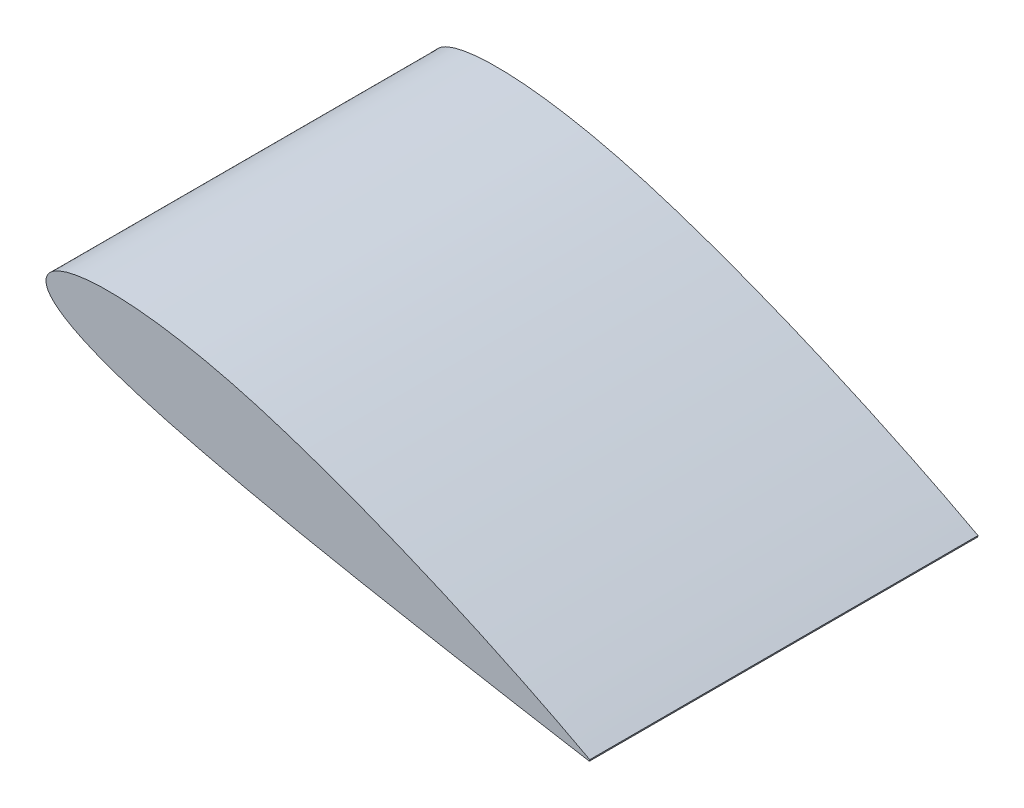
SolidWorks part; units mm, degrees
ref_plane "Płaszczyzna przednia"
ref_plane "Płaszczyzna górna" through (0, 0, 0) normal (0, 1, 0) x (1, 0, 0)
ref_plane "Płaszczyzna prawa" through (0, 0, 0) normal (1, 0, 0) x (0, 0, -1)
curve "Krzywa1"
  spline degree 3 poles (1, 0.0015, 0) (0.9991, 0.0017, 0) (0.9956, 0.0025, 0) (0.9875, 0.0044, 0) (0.9742, 0.0074, 0) (0.9556, 0.0115, 0) (0.9322, 0.0166, 0) (0.904, 0.0224, 0) (0.8713, 0.0289, 0) (0.8346, 0.0358, 0) (0.7942, 0.043, 0) (0.7505, 0.0503, 0) (0.7041, 0.0574, 0) (0.6553, 0.0643, 0) (0.6048, 0.0707, 0) (0.5531, 0.0765, 0) (0.5007, 0.0814, 0) (0.4483, 0.0853, 0) (0.3962, 0.0881, 0) (0.3451, 0.0894, 0) (0.2956, 0.089, 0) (0.2483, 0.0868, 0) (0.2039, 0.083, 0) (0.1628, 0.0776, 0) (0.1256, 0.0708, 0) (0.0927, 0.0627, 0) (0.0643, 0.0537, 0) (0.0409, 0.0439, 0) (0.0225, 0.0337, 0) (0.0093, 0.0231, 0) (0.0011, 0.0119, 0) (-0.001, -0.0001, 0) (0.0034, -0.0114, 0) (0.0135, -0.0208, 0) (0.0284, -0.0287, 0) (0.0479, -0.0355, 0) (0.0722, -0.0411, 0) (0.1009, -0.0456, 0) (0.1337, -0.0489, 0) (0.1703, -0.0511, 0) (0.2104, -0.0521, 0) (0.2535, -0.0522, 0) (0.2992, -0.0514, 0) (0.347, -0.0499, 0) (0.3967, -0.0479, 0) (0.4476, -0.0455, 0) (0.4993, -0.0424, 0) (0.5511, -0.0389, 0) (0.6024, -0.0352, 0) (0.6526, -0.0314, 0) (0.7012, -0.0275, 0) (0.7477, -0.0237, 0) (0.7915, -0.0201, 0) (0.8321, -0.0166, 0) (0.8691, -0.0134, 0) (0.9021, -0.0105, 0) (0.9307, -0.0079, 0) (0.9546, -0.0057, 0) (0.9734, -0.004, 0) (0.9871, -0.0027, 0) (0.9953, -0.0019, 0) (0.999, -0.0016, 0) (1, -0.0015, 0) knots 0 0 0 0 0.001308 0.005358 0.012063 0.021337 0.033087 0.047171 0.063441 0.081714 0.101785 0.123442 0.146433 0.170517 0.195424 0.220875 0.246594 0.272302 0.297725 0.322799 0.347029 0.370162 0.391954 0.412188 0.43067 0.447231 0.461732 0.474085 0.484276 0.492392 0.498749 0.5041 0.509453 0.51579 0.523838 0.533885 0.546005 0.560171 0.576284 0.594211 0.613803 0.634869 0.65721 0.680611 0.704835 0.729853 0.755197 0.780583 0.805729 0.830359 0.854204 0.877002 0.898494 0.918443 0.936623 0.952826 0.966868 0.978592 0.987852 0.994547 0.998596 1 1 1 1
sketch "Szkic1" plane through (0, 0, 0) normal (0, 0, 1) x (1, 0, 0)
  line L0 (699.9029, -187.9268) -> (699.3515, -189.9846)
  line L1 (16.3522, 61.0271) -> (716.3522, -126.5373) construction
  line L2 (16.3522, 61.0271) -> (-10.1518, -37.8869) construction
  line L3 (-10.1518, -37.8869) -> (689.8482, -225.4513) construction
  line L4 (716.3522, -126.5373) -> (689.8482, -225.4513) construction
  line L5 (500.002, 0) -> (0, 0) construction
  line L6 (0, 0) -> (-68.0941, 0) construction
  spline S1 degree 3 poles (699.9029, -187.9268) (699.3338, -187.6158) (697.0031, -186.3423) (691.7065, -183.5667) (682.9295, -178.9272) (670.7346, -172.5873) (655.2545, -164.638) (628.5192, -151.1881) (588.2383, -131.6047) (532.7177, -105.9919) (480.9854, -83.605) (436.2712, -65.3508) (401.1493, -51.6181) (365.4184, -38.3681) (329.4605, -25.7883) (293.553, -14.0525) (258.0259, -3.5507) (223.2564, 5.4375) (189.7682, 12.7935) (157.9576, 18.4364) (128.2117, 22.3636) (100.8867, 24.5535) (76.3194, 25.11) (54.802, 24.1005) (36.5732, 21.6739) (21.7891, 17.9428) (10.5315, 12.9957) (2.7101, 6.7112) (-1.054, -1.2885) (-0.0411, -10.0548) (5.2736, -18.5019) (14.1664, -26.8186) (26.5992, -35.2437) (42.503, -43.7397) (61.7352, -52.2482) (84.0856, -60.7229) (109.3218, -69.1001) (137.1666, -77.3557) (167.3165, -85.4957) (199.449, -93.508) (233.212, -101.4338) (268.3422, -109.3342) (304.4727, -117.1729) (341.2523, -124.7255) (378.1503, -132.0087) (426.3432, -141.2753) (483.8084, -151.9375) (538.7793, -161.9184) (586.9036, -170.5039) (620.2773, -176.4053) (649.654, -181.4963) (666.7624, -184.4505) (680.2877, -186.7538) (690.062, -188.4198) (696.003, -189.4023) (698.6658, -189.8653) (699.3515, -189.9846) knots 0 0 0 0 0.001308 0.005358 0.012063 0.021337 0.033087 0.047171 0.081714 0.123442 0.170517 0.195424 0.220875 0.246594 0.272302 0.297725 0.322799 0.347029 0.370162 0.391954 0.412188 0.43067 0.447231 0.461732 0.474085 0.484276 0.492392 0.498749 0.5041 0.509453 0.51579 0.523838 0.533885 0.546005 0.560171 0.576284 0.594211 0.613803 0.634869 0.65721 0.680611 0.704835 0.729853 0.755197 0.780583 0.805729 0.854204 0.898494 0.918443 0.952826 0.966868 0.978592 0.987852 0.994547 0.998596 1 1 1 1
  point P9 (0, 0)
  point P11 (500, -27.0621)
  dimension "D1" = 90
  dimension "D2" = 90
  dimension "D3" = 90
  dimension "D4" = 700
  dimension "D5" = 75
extrude "Dodanie-wyciągnięcie2" add sketch "Szkic1" along normal blind 500
